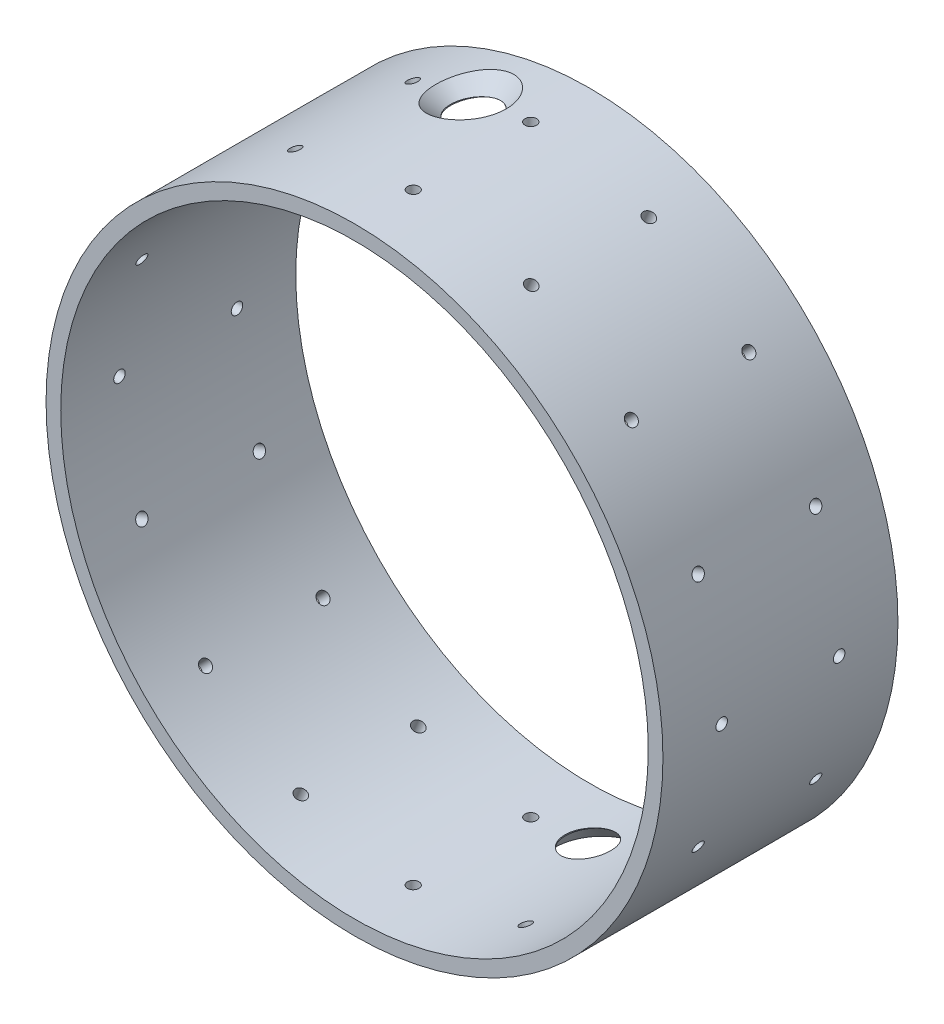
SolidWorks part; units mm, degrees
material "6061-T6 (SS)"
ref_plane "Front Plane" through (0, 0, 0) normal (0, 0, 1) x (1, 0, 0)
ref_plane "Top Plane" through (0, 0, 0) normal (0, 1, 0) x (1, 0, 0)
ref_plane "Right Plane" through (0, 0, 0) normal (1, 0, 0) x (0, 0, -1)
sketch "Sketch1" plane through (0, 0, 0) normal (0, 0, 1) x (1, 0, 0)
  circle A0 centre (0, 0) radius 63.5
  circle A1 centre (0, 0) radius 66.675
extrude "Extrude1" add sketch "Sketch1" along normal blind 50.8
ref_plane "Plane1" through (0, 0, 12.7) normal (0, 0, -1) x (-1, 0, 0)
sketch "Sketch2" plane through (0, 0, 12.7) normal (0, 0, -1) x (-1, 0, 0)
  line L0 (0, 0) -> (0, 66.675) construction
  line L1 (0, 0) -> (13.0076, 65.3939) construction
  circle A0 centre (0, 0) radius 66.675 construction
  dimension "D1" = 11.25
ref_plane "Plane4" through (0, 66.675, 12.7) normal (0, 1, 0) x (-1, 0, 0)
sketch "Sketch7" plane through (0, 66.675, 12.7) normal (0, 1, 0) x (-1, 0, 0)
  line L0 (0, 0) -> (0, 25.4) construction
hole_wizard "#40 (0.098) Diameter Hole2" positions "Sketch9" profile "Sketch8" hole size "#40" standard "Ansi Inch"
sketch "Sketch9" plane through (0, 66.675, 12.7) normal (0, 1, 0) x (-1, 0, 0)
  point P1 (0, 0)
  point P4 (0, 25.4)
sketch "Sketch8" plane through (0, 66.675, 12.7) normal (1, 0, 0) x (0, 0, 1)
  line L0 (0, 0) -> (0, 13.4478)
  line L1 (0, 13.4478) -> (1.2446, 12.7)
  line L2 (1.2446, 12.7) -> (1.2446, 0)
  line L5 (1.2446, 0) -> (0, 0)
  line L10 (0, 13.4478) -> (-1.2446, 12.7) construction
  line L11 (0, -6.35) -> (0, 107.95) construction
  dimension "Hole Dia." = 2.4892
  dimension "Hole Depth" = 12.7
  dimension "Drill Angle" = 118
pattern_circular "CirPattern1" count 16 over 360 about axis through (0, 0, 50.8) along (0, 0, -1) of "#40 (0.098) Diameter Hole2"
ref_plane "Plane5" through (-13.0076, 65.3939, 12.7) normal (-0.1951, 0.9808, 0) x (-0.9808, -0.1951, 0)
hole_wizard "3/8 Clearance Hole1" positions "Sketch13" profile "Sketch14" hole size "3/8" standard "Ansi Inch"
sketch "Sketch13" plane through (-13.0076, 65.3939, 12.7) normal (-0.1951, 0.9808, 0) x (-0.9808, -0.1951, 0)
  point P1 (0, 0)
sketch "Sketch14" plane through (-13.0076, 65.3939, 12.7) normal (0, 0, 1) x (-0.9808, -0.1951, 0)
  line L0 (0, 0) -> (0, 15.9835)
  line L1 (0, 15.9835) -> (5.0419, 12.954)
  line L2 (5.0419, 12.954) -> (5.0419, 3.175)
  line L3 (5.0419, 3.175) -> (8.2169, 0)
  line L5 (8.2169, 0) -> (0, 0)
  line L6 (-5.0419, 3.175) -> (-8.2169, 0) construction
  line L10 (0, 15.9835) -> (-5.0419, 12.954) construction
  line L11 (0, -6.35) -> (0, 107.95) construction
  dimension "Hole Dia." = 10.0838
  dimension "Hole Depth" = 12.954
  dimension "Near C'Sink Dia." = 16.4338
  dimension "Near C'Sink Angle" = 90
  dimension "Drill Angle" = 118
ref_plane "Plane6" through (0, 0, 12.7) normal (-0.1951, 0.9808, 0) x (-0.9808, -0.1951, 0)
mirror "Mirror1" about plane through (0, 0, 12.7) normal (-0.1951, 0.9808, 0) of "3/8 Clearance Hole1"
